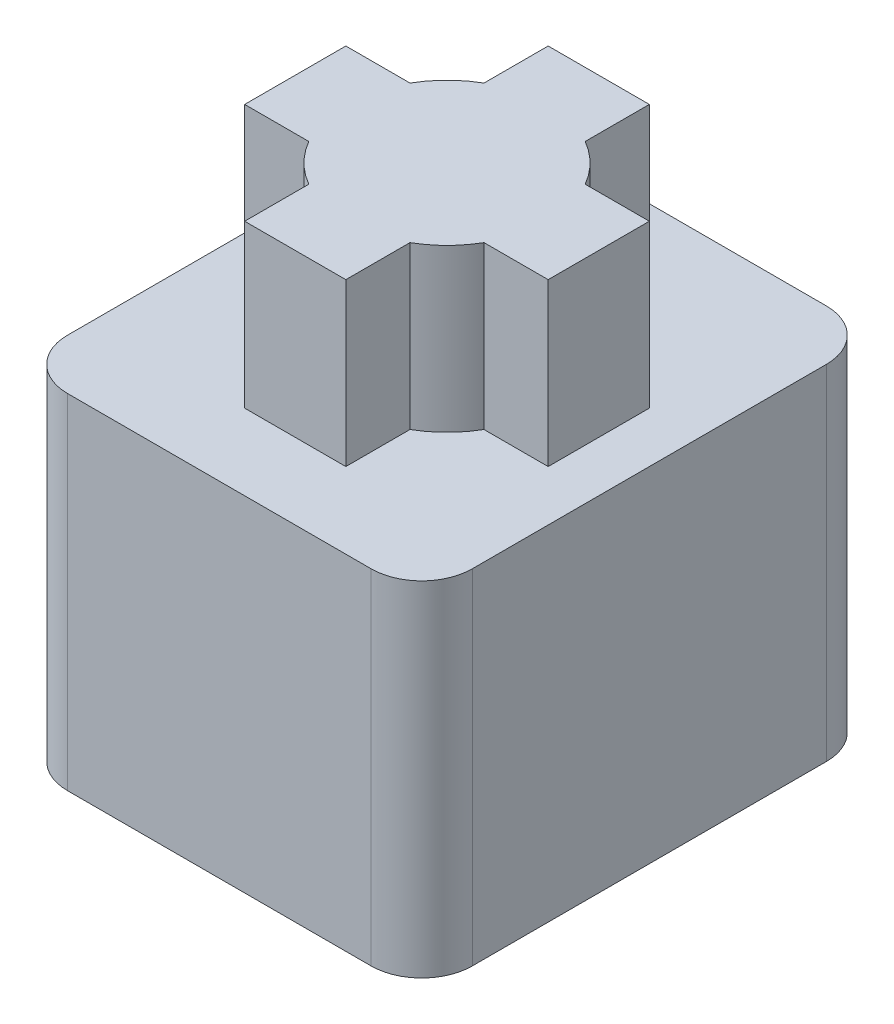
SolidWorks part; units mm, degrees
ref_plane "Front Plane" through (0, 0, 0) normal (0, 0, 1) x (1, 0, 0)
ref_plane "Top Plane" through (0, 0, 0) normal (0, 1, 0) x (1, 0, 0)
ref_plane "Right Plane" through (0, 0, 0) normal (1, 0, 0) x (0, 0, -1)
sketch "Sketch2" plane through (0, 0, 0) normal (0, 1, 0) x (1, 0, 0)
  line L1 (0, 0) -> (8, 0)
  line L2 (0, 0) -> (0, 9)
  line L3 (0, 9) -> (8, 9)
  line L4 (8, 0) -> (8, 9)
  dimension "D1" = 8
  dimension "D2" = 9
extrude "Boss-Extrude1" add sketch "Sketch2" along normal blind 6.8
fillet "Fillet1" radius 1 4 edges at (0, 3.4, -9) (8, 3.4, -9) (0, 3.4, 0) (8, 3.4, 0)
sketch "Sketch3" plane through (0, 6.8, 0) normal (0, 1, 0) x (1, 0, 0)
  line L0 (8, 1) -> (8, 8) construction
  line L1 (1, 0) -> (7, 0) construction
  line L3 (3, 7.5) -> (5, 7.5)
  line L4 (3, 7.5) -> (3, 1.5)
  line L5 (3, 1.5) -> (5, 1.5)
  line L6 (5, 7.5) -> (5, 1.5)
  line L7 (3, 7.5) -> (5, 1.5) construction
  line L8 (3, 1.5) -> (5, 7.5) construction
  line L9 (1, 3.5) -> (7, 3.5)
  line L10 (1, 3.5) -> (1, 5.5)
  line L11 (1, 5.5) -> (7, 5.5)
  line L12 (7, 3.5) -> (7, 5.5)
  line L13 (1, 3.5) -> (7, 5.5) construction
  line L14 (1, 5.5) -> (7, 3.5) construction
  circle A0 centre (4, 4.5) radius 2
  dimension "D3" = 4
  dimension "D1" = 4
  dimension "D2" = 4.5
  dimension "D4" = 6
  dimension "D5" = 2
  dimension "D6" = 2
  dimension "D7" = 6
extrude "Boss-Extrude2" add sketch "Sketch3" along normal blind 3.2 contours L11 L4 L9 L6 | L11 A0 L9 L4 | L4 A0 L11 | L6 A0 L4 L11 | L9 A0 L11 L6 | L11 A0 L6 | L4 A0 L6 L9 | L6 A0 L9 | L9 A0 L4 | A0 L4 L5 L6 | A0 L11 L10 L9 | A0 L6 L3 L4 | A0 L9 L12 L11
